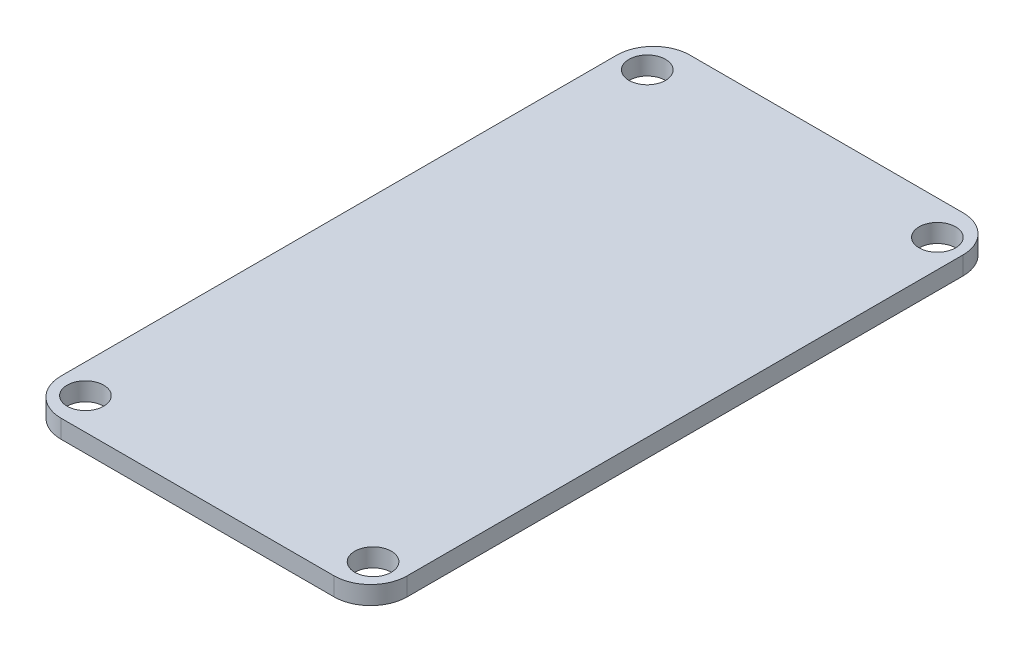
SolidWorks part; units mm, degrees
ref_plane "前视基准面" through (0, 0, 0) normal (0, 0, 1) x (1, 0, 0)
ref_plane "上视基准面" through (0, 0, 0) normal (0, 1, 0) x (1, 0, 0)
ref_plane "右视基准面" through (0, 0, 0) normal (1, 0, 0) x (0, 0, -1)
sketch "Sketch1" plane through (0, 0, 0) normal (0, 1, 0) x (1, 0, 0)
  line L1 (-11.2, 25.8) -> (11.2, 25.8)
  line L2 (-14.2, 22.8) -> (-14.2, -22.8)
  line L3 (-11.2, -25.8) -> (11.2, -25.8)
  line L4 (14.2, 22.8) -> (14.2, -22.8)
  line L5 (-14.2, 25.8) -> (14.2, -25.8) construction
  line L6 (-14.2, -25.8) -> (14.2, 25.8) construction
  arc A0 (-11.2, 25.8) -> (-14.2, 22.8) centre (-11.2, 22.8) ccw
  arc A1 (11.2, 25.8) -> (14.2, 22.8) centre (11.2, 22.8) cw
  arc A2 (11.2, -25.8) -> (14.2, -22.8) centre (11.2, -22.8) ccw
  arc A3 (-14.2, -22.8) -> (-11.2, -25.8) centre (-11.2, -22.8) ccw
  point P0 (0, 0)
  dimension "D3" = 3
  dimension "D1" = 51.6
  dimension "D2" = 28.4
extrude "Boss-Extrude1" add sketch "Sketch1" along normal mid plane 1.5
sketch "Sketch3" plane through (0, 0.75, 0) normal (0, 1, 0) x (1, 0, 0)
  line L1 (0, 25.8) -> (0, -25.8) construction
  line L2 (11.2, 25.8) -> (-11.2, 25.8) construction
  line L3 (-11.2, -25.8) -> (11.2, -25.8) construction
  line L4 (14.2, -22.8) -> (14.2, 22.8) construction
  circle A4 centre (11.9, 23) radius 1.5
  circle A5 centre (-11.9, 23) radius 1.5
  circle A6 centre (11.8, -23.2) radius 1.5
  circle A7 centre (-11.8, -23.2) radius 1.5
  dimension "D1" = 2.8
  dimension "D5" = 3
  dimension "D2" = 2.3
  dimension "D3" = 2.4
  dimension "D4" = 2.6
extrude "Cut-Extrude1" cut sketch "Sketch3" against normal up to next
